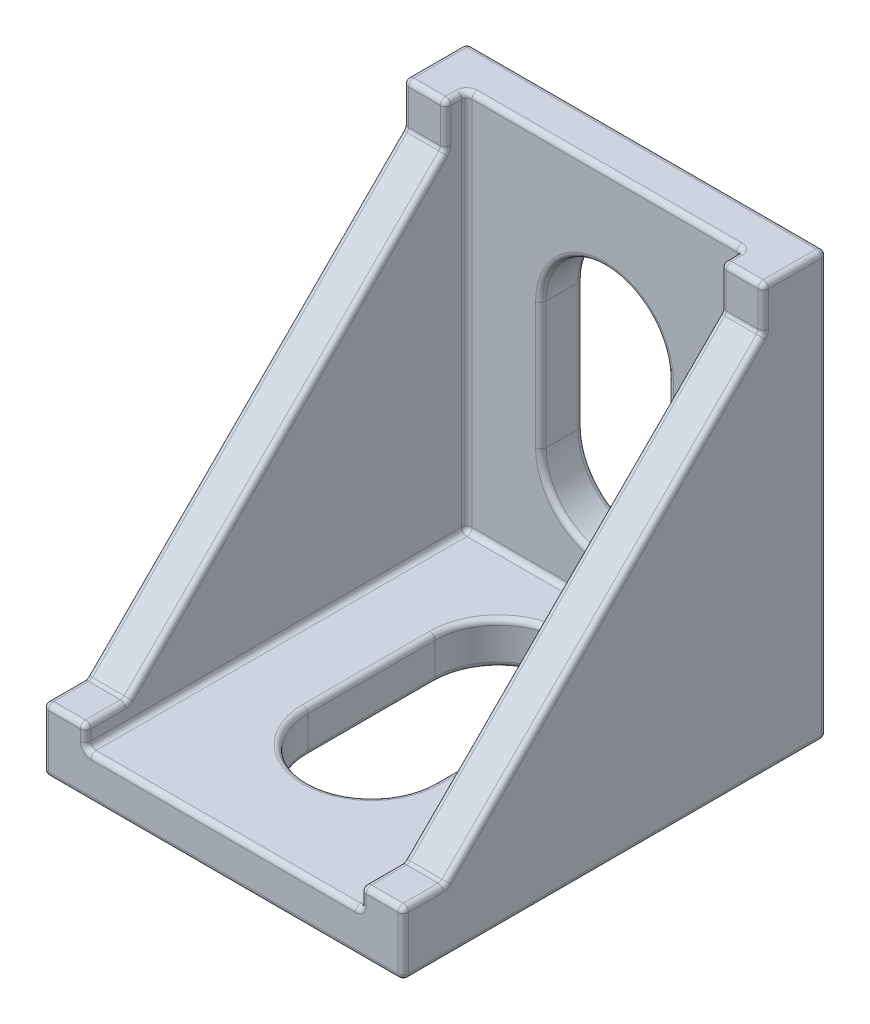
SolidWorks part; units mm, degrees
material "1060 Alloy"
ref_plane "Front Plane" through (0, 0, 0) normal (0, 0, 1) x (1, 0, 0)
ref_plane "Top Plane" through (0, 0, 0) normal (0, 1, 0) x (1, 0, 0)
ref_plane "Right Plane" through (0, 0, 0) normal (1, 0, 0) x (0, 0, -1)
ref_plane "BaseLevelPlane" through (0, 2, 0) normal (0, 1, 0) x (1, 0, 0)
ref_plane "TopLevelPlane" through (0, 20, 0) normal (0, 1, 0) x (1, 0, 0)
ref_plane "Left Side Plane" through (17, 0, 0) normal (1, 0, 0) x (0, 0, -1)
ref_plane "Rear Plane" through (0, 0, -20) normal (0, 0, 1) x (1, 0, 0)
sketch "Master Sketch" plane through (0, 0, 0) normal (0, 1, 0) x (1, 0, 0)
  line L0 (2, 0) -> (2, 18)
  line L1 (0, 0) -> (2, 0)
  line L2 (0, 0) -> (0, 20)
  line L3 (0, 20) -> (17, 20)
  line L4 (17, 0) -> (17, 20)
  line L5 (2, 18) -> (15, 18)
  line L6 (15, 18) -> (15, 0)
  line L7 (15, 0) -> (17, 0)
  line L8 (2, 0) -> (15, 0)
  line L9 (2, 18) -> (2, 20) construction
  line L10 (0, 10) -> (17, 10) construction
  line L11 (7, 19) -> (10, 19)
  line L13 (7, 17) -> (10, 17)
  line L15 (7, 19) -> (10, 17) construction
  line L16 (7, 17) -> (10, 19) construction
  line L17 (7, 1) -> (10, 1)
  line L18 (7, 3) -> (10, 3)
  arc A0 (7, 19) -> (7, 17) centre (7, 18) ccw
  arc A1 (10, 17) -> (10, 19) centre (10, 18) ccw
  arc A2 (7, 1) -> (7, 3) centre (7, 2) cw
  arc A3 (10, 3) -> (10, 1) centre (10, 2) cw
  point P10 (8.5, 18)
  dimension "D4" = 3
  dimension "D5" = 1
  dimension "D1" = 20
  dimension "D2" = 17
  dimension "D3" = 2
  dimension "D6" = 8.5
  dimension "D7" = 18
sketch "Base Sketch" plane through (0, 0, 0) normal (0, 1, 0) x (1, 0, 0)
  line L0 (0, 0) -> (2, 0) construction
  line L1 (2, 0) -> (15, 0) construction
  line L2 (15, 0) -> (17, 0) construction
  line L3 (17, 0) -> (17, 20) construction
  line L4 (0, 20) -> (17, 20) construction
  line L5 (0, 0) -> (0, 20) construction
  line L6 (0, 0) -> (2, 0)
  line L7 (2, 0) -> (15, 0)
  line L8 (15, 0) -> (17, 0)
  line L9 (17, 0) -> (17, 20)
  line L10 (0, 20) -> (17, 20)
  line L11 (0, 0) -> (0, 20)
  line L14 (5.5, 13) -> (5.5, 7)
  line L16 (11.5, 13) -> (11.5, 7)
  line L17 (5.5, 13) -> (11.5, 7) construction
  line L18 (5.5, 7) -> (11.5, 13) construction
  arc A0 (5.5, 13) -> (11.5, 13) centre (8.5, 13) cw
  arc A1 (5.5, 7) -> (11.5, 7) centre (8.5, 7) ccw
  point P2 (8.5, 10)
  dimension "D1" = 6
  dimension "D2" = 6
  dimension "D3" = 8.5
  dimension "D4" = 10
extrude "Base" add sketch "Base Sketch" along normal up to surface (2 mm away) up to plane "BaseLevelPlane"
sketch "MainUprightSketch" plane through (0, 2, 0) normal (0, 1, 0) x (1, 0, 0)
  line L0 (17, 0) -> (17, 20) construction
  line L1 (15, 0) -> (17, 0) construction
  line L2 (15, 18) -> (15, 0) construction
  line L3 (2, 18) -> (15, 18) construction
  line L4 (0, 20) -> (17, 20) construction
  line L5 (0, 0) -> (2, 0) construction
  line L6 (2, 0) -> (2, 18) construction
  line L7 (0, 0) -> (0, 20) construction
  line L8 (17, 0) -> (17, 20)
  line L9 (15, 0) -> (17, 0)
  line L10 (15, 18) -> (15, 0)
  line L11 (2, 18) -> (15, 18)
  line L12 (0, 20) -> (17, 20)
  line L13 (0, 0) -> (2, 0)
  line L14 (2, 0) -> (2, 18)
  line L15 (0, 0) -> (0, 20)
extrude "Sides" add sketch "MainUprightSketch" along normal up to surface (18 mm away) up to plane "TopLevelPlane"
sketch "NubsSketch" plane through (0, 0, 0) normal (0, 1, 0) x (1, 0, 0)
  line L0 (7, 19) -> (10, 19) construction
  line L1 (7, 17) -> (10, 17) construction
  line L2 (7, 1) -> (10, 1) construction
  line L3 (7, 3) -> (10, 3) construction
  line L4 (7, 19) -> (10, 19)
  line L5 (7, 17) -> (10, 17)
  line L6 (7, 1) -> (10, 1)
  line L7 (7, 3) -> (10, 3)
  arc A0 (7, 19) -> (7, 17) centre (7, 18) ccw construction
  arc A1 (10, 17) -> (10, 19) centre (10, 18) ccw construction
  arc A2 (10, 1) -> (10, 3) centre (10, 2) ccw construction
  arc A3 (7, 3) -> (7, 1) centre (7, 2) ccw construction
  arc A4 (7, 19) -> (7, 17) centre (7, 18) ccw
  arc A5 (10, 17) -> (10, 19) centre (10, 18) ccw
  arc A6 (10, 1) -> (10, 3) centre (10, 2) ccw
  arc A7 (7, 3) -> (7, 1) centre (7, 2) ccw
extrude "Nubs-Bottom" add sketch "NubsSketch" against normal blind 1
sketch "RearNubsSketch" plane through (0, 0, -20) normal (0, 0, 1) x (1, 0, 0)
  line L0 (7, 0) -> (10, 0) construction
  line L1 (7, 0) -> (10, 0) construction
  line L3 (10, 3) -> (7, 3)
  line L5 (10, 1) -> (7, 1)
  line L7 (10, 3) -> (7, 1) construction
  line L8 (10, 1) -> (7, 3) construction
  line L9 (17, 10) -> (0, 10) construction
  line L10 (10, 19) -> (7, 19)
  line L11 (10, 17) -> (7, 17)
  arc A0 (10, 3) -> (10, 1) centre (10, 2) cw
  arc A1 (7, 1) -> (7, 3) centre (7, 2) cw
  arc A2 (10, 17) -> (10, 19) centre (10, 18) ccw
  arc A3 (7, 19) -> (7, 17) centre (7, 18) ccw
  point P2 (8.5, 2)
  dimension "D1" = 1
  dimension "D2" = 10
  dimension "D3" = 2
extrude "Nubs-Rear" add sketch "RearNubsSketch" against normal blind 1
sketch "Cutaway Sketch" plane through (0, 0, 0) normal (1, 0, 0) x (0, 0, -1)
  line L1 (0, 3) -> (2, 3)
  line L2 (2, 3) -> (17, 18)
  line L3 (17, 18) -> (17, 20)
  line L6 (17, 20) -> (0, 20)
  line L7 (0, 20) -> (0, 3)
  dimension "D1" = 3
  dimension "D2" = 20
  dimension "D3" = 2
  dimension "D4" = 45
extrude "Side Cut" cut sketch "Cutaway Sketch" along normal up to surface (17 mm away) up to plane "Left Side Plane"
sketch "RearSlotSketch" plane through (0, 0, -20) normal (0, 0, 1) x (1, 0, 0)
  line L2 (5.5, 13) -> (5.5, 7)
  line L4 (11.5, 13) -> (11.5, 7)
  line L5 (5.5, 13) -> (11.5, 7) construction
  line L6 (5.5, 7) -> (11.5, 13) construction
  arc A0 (5.5, 13) -> (11.5, 13) centre (8.5, 13) cw
  arc A1 (5.5, 7) -> (11.5, 7) centre (8.5, 7) ccw
  point P0 (8.5, 10)
  dimension "D1" = 3
  dimension "D2" = 6
  dimension "D3" = 10
  dimension "D4" = 8.5
extrude "Rear Slot" cut sketch "RearSlotSketch" along normal through all
fillet "Cosmetic Fillets" radius 0.25 90 edges at (8.5, 1, -21) (11, 2, -21) (8.5, 3, -21) (6, 2, -21) (8.5, 19, -21) (6, 18, -21) (8.5, 17, -21) (11, 18, -21) (5.5, 10, -20) (8.5, 16, -20) (11.5, 10, -20) (8.5, 4, -20) (6, 18, -20) (8.5, 19, -20) (11, 18, -20) (8.5, 17, -20) (11, 2, -20) (8.5, 1, -20) (6, 2, -20) (8.5, 3, -20) (0, 10, -20) (0, 19, -17) (0, 3, -1) (1, 3, -2) (0, 10.5, -9.5) (1, 18, -17) (16, 3, 0) (0, 1.5, 0) (1, 3, 0) (16, 18, -17) (16, 3, -2) (8.5, 20, -20) (16, 20, -17) (1, 20, -17) (0, 20, -18.5) (17, 10.5, -9.5) (17, 19, -17) (17, 20, -18.5) (17, 10, -20) (17, 1.5, 0) (17, 3, -1) (15, 2.5, 0) (15, 20, -17.5) (15, 19, -17) (15, 10.5, -9.5) (15, 3, -1) (11.5, 10, -18) (8.5, 16, -18) (5.5, 10, -18) (8.5, 4, -18) (15, 11, -18) (8.5, 20, -18) (2, 10.5, -9.5) (2, 19, -17) (2, 20, -17.5) (2, 11, -18) (2, 2.5, 0) (2, 3, -1) (11.5, 2, -10) (8.5, 2, -16) (5.5, 2, -10) (8.5, 2, -4) (8.5, 2, 0) (2, 2, -9) (8.5, 2, -18) (15, 2, -9) (8.5, -1, -17) (11, -1, -18) (8.5, -1, -19) (6, -1, -18) (8.5, -1, -3) (6, -1, -2) (8.5, -1, -1) (11, -1, -2) (8.5, 0, -16) (11.5, 0, -10) (8.5, 0, -4) (5.5, 0, -10) (8.5, 0, 0) (17, 0, -10) (8.5, 0, -20) (0, 0, -10) (8.5, 0, -19) (11, 0, -18) (8.5, 0, -17) (6, 0, -18) (8.5, 0, -1) (6, 0, -2) (8.5, 0, -3) (11, 0, -2)
